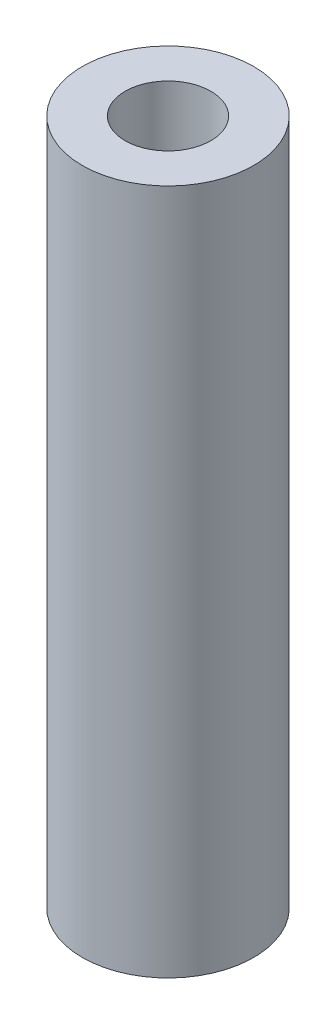
SolidWorks part; units mm, degrees
ref_plane "Front Plane" through (0, 0, 0) normal (0, 0, 1) x (1, 0, 0)
ref_plane "Top Plane" through (0, 0, 0) normal (0, 1, 0) x (1, 0, 0)
ref_plane "Right Plane" through (0, 0, 0) normal (1, 0, 0) x (0, 0, -1)
sketch "Sketch1" plane through (0, 0, 0) normal (0, 1, 0) x (1, 0, 0)
  circle A0 centre (0, 0) radius 1.5875
  circle A1 centre (0, 0) radius 3.175
extrude "Boss-Extrude1" add sketch "Sketch1" along normal blind 25.4
